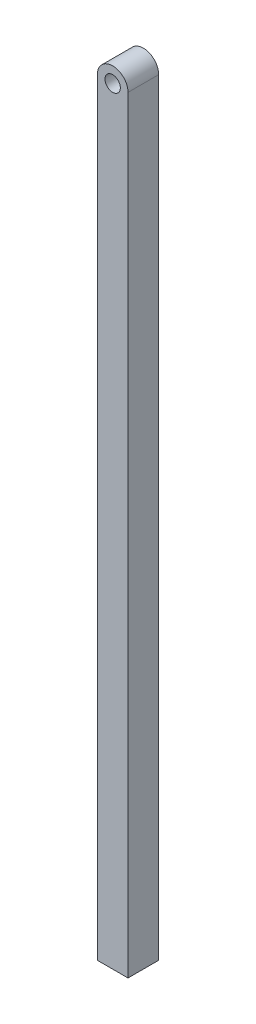
SolidWorks part; units mm, degrees
material "Plain Carbon Steel"
ref_plane "Front Plane" through (0, 0, 0) normal (0, 0, 1) x (1, 0, 0)
ref_plane "Top Plane" through (0, 0, 0) normal (0, 1, 0) x (1, 0, 0)
ref_plane "Right Plane" through (0, 0, 0) normal (1, 0, 0) x (0, 0, -1)
sketch "Sketch1" plane through (0, 0, 0) normal (0, 0, 1) x (1, 0, 0)
  line L0 (-12.7, 0) -> (-12.7, -635)
  line L1 (-12.7, -635) -> (12.7, -635)
  line L2 (12.7, -635) -> (12.7, 0)
  circle A0 centre (0, 0) radius 6.35
  arc A1 (12.7, 0) -> (-12.7, 0) centre (0, 0) ccw
  dimension "D1" = 12.7
  dimension "D2" = 25.4
  dimension "D3" = 635
extrude "Boss-Extrude1" add sketch "Sketch1" along normal blind 25.4
